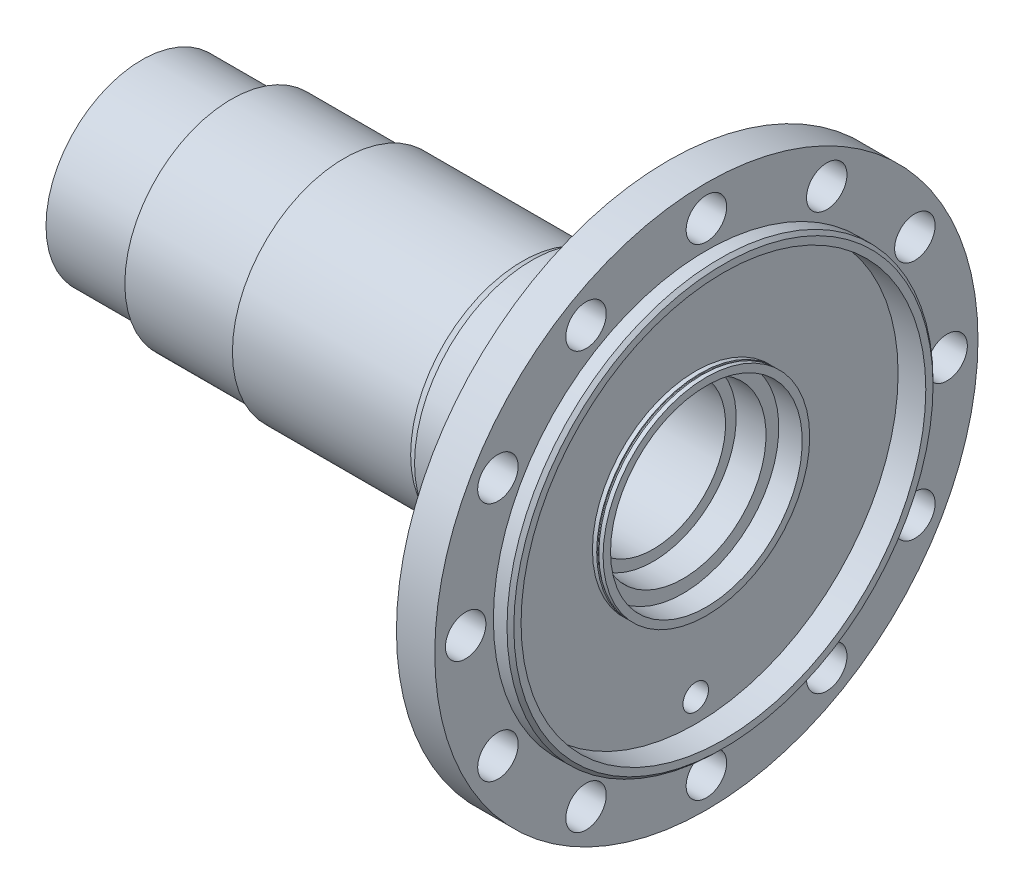
SolidWorks part; units mm, degrees
ref_plane "Спереди" through (0, 0, 0) normal (0, 0, 1) x (1, 0, 0)
ref_plane "Сверху" through (0, 0, 0) normal (0, 1, 0) x (1, 0, 0)
ref_plane "Справа" through (0, 0, 0) normal (1, 0, 0) x (0, 0, -1)
sketch "Эскиз1" plane through (0, 0, 0) normal (0, 0, 1) x (1, 0, 0)
  line L0 (0, 0) -> (273, 0)
  line L1 (0, 0) -> (0, 45)
  line L2 (0, 45) -> (42, 45)
  line L3 (42, 45) -> (42, 50)
  line L4 (42, 50) -> (95, 50)
  line L5 (95, 50) -> (95, 52.5)
  line L6 (95, 52.5) -> (178.6699, 52.5)
  line L7 (178.6699, 52.5) -> (183, 55)
  line L8 (183, 55) -> (215, 55)
  line L9 (215, 55) -> (215, 62.5)
  line L10 (215, 62.5) -> (239, 62.5)
  line L11 (239, 62.5) -> (239, 100)
  line L12 (239, 100) -> (247, 100)
  line L13 (247, 100) -> (247, 127.5)
  line L14 (247, 127.5) -> (265, 127.5)
  line L15 (265, 127.5) -> (265, 100)
  line L16 (265, 100) -> (271.4, 100)
  line L17 (271.4, 100) -> (273, 98.4)
  line L18 (273, 98.4) -> (273, 0)
revolve "Повернуть1" add sketch "Эскиз1" angle 360 about L0
sketch "Эскиз2" plane through (0, 0, 0) normal (0, 0, 1) x (1, 0, 0)
  line L0 (0, 0) -> (273, 0)
  line L1 (0, 0) -> (0, 31)
  line L2 (0, 31) -> (203.5, 31)
  line L3 (203.5, 31) -> (203.5, 34)
  line L4 (203.5, 34) -> (240, 34)
  line L5 (240, 34) -> (240, 39)
  line L6 (240, 39) -> (254, 39)
  line L7 (254, 39) -> (254, 45)
  line L8 (254, 45) -> (265, 45)
  line L9 (265, 45) -> (265, 95)
  line L10 (265, 95) -> (273, 95)
  line L11 (273, 95) -> (273, 0)
revolve "Вырез-Повернуть1" cut sketch "Эскиз2" angle 360 about L0
sketch "Эскиз3" plane through (0, 0, 0) normal (0, 0, 1) x (1, 0, 0)
  line L0 (0, 0) -> (273, 0) construction
  line L1 (260, 48.5) -> (262, 48.5)
  line L2 (262, 48.5) -> (262, 95)
  line L3 (262, 95) -> (260, 95)
  line L4 (260, 95) -> (260, 48.5)
revolve "Rear_recess_left" cut sketch "Эскиз3" angle 360 about L0
sketch "Эскиз4" plane through (0, 0, 0) normal (0, 0, 1) x (1, 0, 0)
  line L0 (0, 0) -> (273, 0) construction
  line L1 (263, 48) -> (263, 95)
  line L2 (263, 95) -> (262, 95)
  line L3 (262, 95) -> (262, 48)
  arc A0 (262, 48) -> (262.5, 47.5) centre (262.5, 48) ccw
  arc A1 (262.5, 47.5) -> (263, 48) centre (262.5, 48) ccw
revolve "Collar_groove_nominal" cut sketch "Эскиз4" angle 360 about L0
sketch "Эскиз5" plane through (0, 0, 0) normal (0, 0, 1) x (1, 0, 0)
  line L0 (0, 0) -> (273, 0) construction
  line L1 (263, 48.5) -> (265, 48.5)
  line L2 (265, 48.5) -> (265, 95)
  line L3 (265, 95) -> (263, 95)
  line L4 (263, 95) -> (263, 48.5)
revolve "Rear_recess_lip" cut sketch "Эскиз5" angle 360 about L0
sketch "Эскиз6" plane through (0, 0, 0) normal (1, 0, 0) x (0, 0, -1)
  circle A0 centre (0, 113) radius 9.5
extrude "Вырез-Вытянуть1" cut sketch "Эскиз6" along normal through all
sketch "Эскиз7" plane through (0, 0, 0) normal (1, 0, 0) x (0, 0, -1)
  circle A0 centre (-56.5, 97.8609) radius 9.5
extrude "Вырез-Вытянуть2" cut sketch "Эскиз7" along normal through all
sketch "Эскиз8" plane through (0, 0, 0) normal (1, 0, 0) x (0, 0, -1)
  circle A0 centre (-97.8609, 56.5) radius 9.5
extrude "Вырез-Вытянуть3" cut sketch "Эскиз8" along normal through all
sketch "Эскиз9" plane through (0, 0, 0) normal (1, 0, 0) x (0, 0, -1)
  circle A0 centre (-113, 0) radius 9.5
extrude "Вырез-Вытянуть4" cut sketch "Эскиз9" along normal through all
sketch "Эскиз10" plane through (0, 0, 0) normal (1, 0, 0) x (0, 0, -1)
  circle A0 centre (-97.8609, -56.5) radius 9.5
extrude "Вырез-Вытянуть5" cut sketch "Эскиз10" along normal through all
sketch "Эскиз11" plane through (0, 0, 0) normal (1, 0, 0) x (0, 0, -1)
  circle A0 centre (-56.5, -97.8609) radius 9.5
extrude "Вырез-Вытянуть6" cut sketch "Эскиз11" along normal through all
sketch "Эскиз12" plane through (0, 0, 0) normal (1, 0, 0) x (0, 0, -1)
  circle A0 centre (0, -113) radius 9.5
extrude "Вырез-Вытянуть7" cut sketch "Эскиз12" along normal through all
sketch "Эскиз13" plane through (0, 0, 0) normal (1, 0, 0) x (0, 0, -1)
  circle A0 centre (56.5, -97.8609) radius 9.5
extrude "Вырез-Вытянуть8" cut sketch "Эскиз13" along normal through all
sketch "Эскиз14" plane through (0, 0, 0) normal (1, 0, 0) x (0, 0, -1)
  circle A0 centre (97.8609, -56.5) radius 9.5
extrude "Вырез-Вытянуть9" cut sketch "Эскиз14" along normal through all
sketch "Эскиз15" plane through (0, 0, 0) normal (1, 0, 0) x (0, 0, -1)
  circle A0 centre (113, 0) radius 9.5
extrude "Вырез-Вытянуть10" cut sketch "Эскиз15" along normal through all
sketch "Эскиз16" plane through (0, 0, 0) normal (1, 0, 0) x (0, 0, -1)
  circle A0 centre (97.8609, 56.5) radius 9.5
extrude "Вырез-Вытянуть11" cut sketch "Эскиз16" along normal through all
sketch "Эскиз17" plane through (0, 0, 0) normal (1, 0, 0) x (0, 0, -1)
  circle A0 centre (56.5, 97.8609) radius 9.5
extrude "Вырез-Вытянуть12" cut sketch "Эскиз17" along normal through all
sketch "Эскиз18" plane through (0, 0, 0) normal (1, 0, 0) x (0, 0, -1)
  circle A0 centre (0, -84) radius 6
extrude "Вырез-Вытянуть13" cut sketch "Эскиз18" along normal through all
